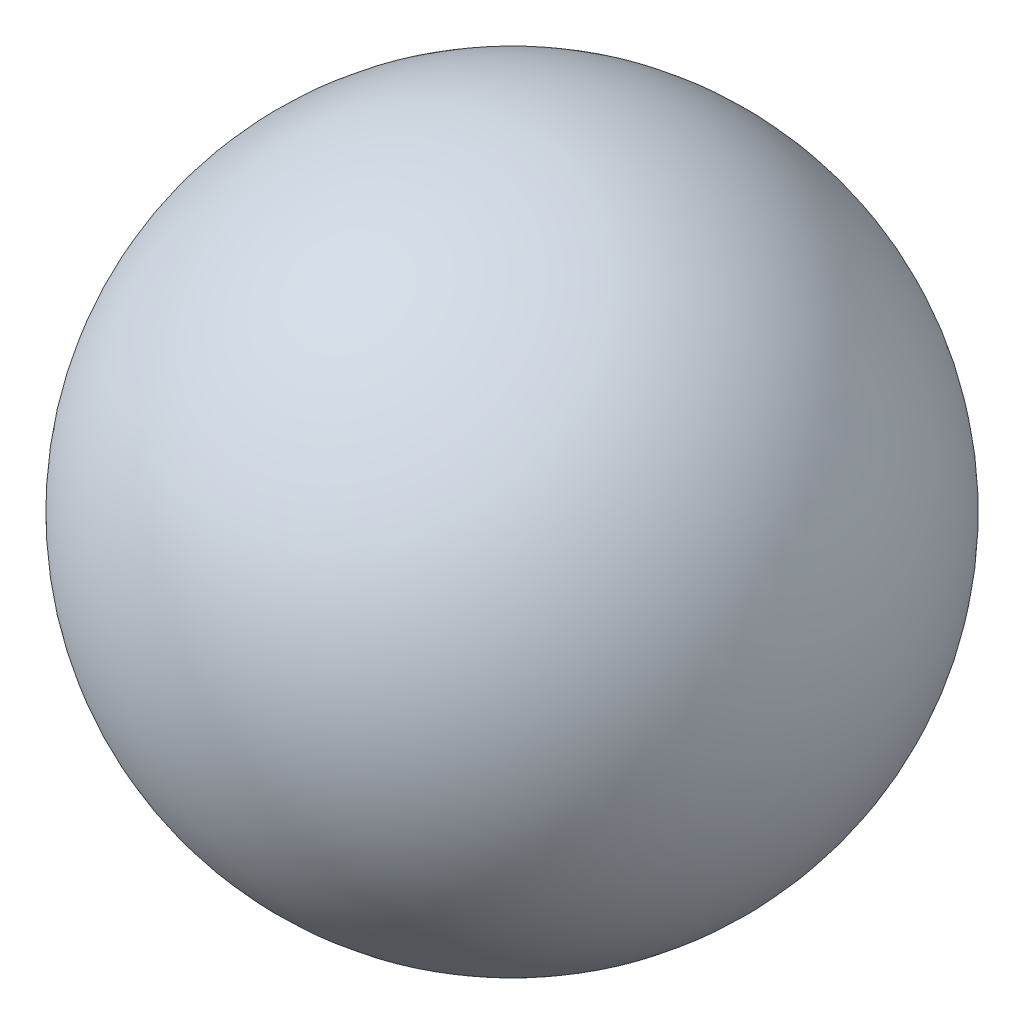
SolidWorks part; units mm, degrees
ref_plane "Front Plane" through (0, 0, 0) normal (0, 0, 1) x (1, 0, 0)
ref_plane "Top Plane" through (0, 0, 0) normal (0, 1, 0) x (1, 0, 0)
ref_plane "Right Plane" through (0, 0, 0) normal (1, 0, 0) x (0, 0, -1)
sketch "Sketch1" plane through (0, 0, 0) normal (0, 0, 1) x (1, 0, 0)
  line L0 (0, 88.9) -> (0, -88.9)
  arc A0 (0, -88.9) -> (0, 88.9) centre (0, 0) ccw
  dimension "D1" = 177.8
revolve "Revolve1" add sketch "Sketch1" angle 360 about L0
